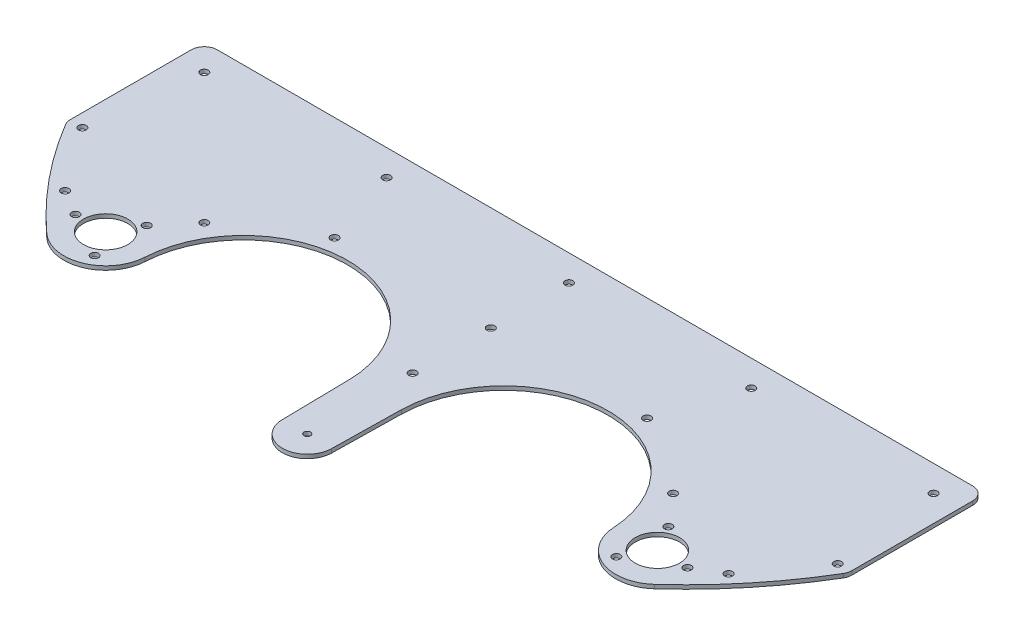
SolidWorks part; units mm, degrees
material "3.0205 (EN-AW 1200)"
ref_plane "Plan de face" through (0, 0, 0) normal (0, 0, 1) x (1, 0, 0)
ref_plane "Plan de dessus" through (0, 0, 0) normal (0, 1, 0) x (1, 0, 0)
ref_plane "Plan de droite" through (0, 0, 0) normal (1, 0, 0) x (0, 0, -1)
sketch "Esquisse1" plane through (0, 0, 0) normal (0, 1, 0) x (1, 0, 0)
  line L0 (0, 0) -> (0, -155) construction
  line L1 (-150, -35) -> (150, -35)
  line L2 (-150, -35) -> (-150, -87.758)
  line L3 (-150, -155) -> (0, -155) construction
  line L7 (-10.0061, -119.3019) -> (-9.5467, -145.6184)
  line L8 (10.0061, -119.3019) -> (9.5467, -145.6184)
  line L11 (150, -35) -> (150, -87.758)
  circle A0 centre (-70, -45) radius 1.5
  circle A1 centre (0, -45) radius 1.5
  circle A2 centre (105.917, -116.9526) radius 8.5
  arc A3 (150, -87.758) -> (116.6574, -128.812) centre (0, 0) cw
  arc A4 (116.6574, -128.812) -> (89.9407, -117.8233) centre (105.917, -116.9526) cw
  circle A5 centre (-105.917, -116.9526) radius 8.5
  circle A6 centre (-100.1435, -106.9526) radius 1.5
  circle A7 centre (70, -45) radius 1.5
  circle A8 centre (-100.1435, -126.9526) radius 1.5
  circle A9 centre (-117.464, -116.9526) radius 1.5
  circle A10 centre (100.1435, -126.9526) radius 1.5
  circle A11 centre (117.464, -116.9526) radius 1.5
  circle A12 centre (-140, -45) radius 1.5
  circle A13 centre (140, -45) radius 1.5
  arc A14 (-9.5467, -145.6184) -> (9.5467, -145.6184) centre (0, -145.4518) ccw
  arc A15 (-116.6574, -128.812) -> (-89.9407, -117.8233) centre (-105.917, -116.9526) ccw
  arc A16 (-150, -87.758) -> (-116.6574, -128.812) centre (0, 0) ccw
  arc A17 (-10.0061, -119.3019) -> (-89.9407, -117.8233) centre (-50, -120) ccw
  arc A18 (10.0061, -119.3019) -> (89.9407, -117.8233) centre (50, -120) cw
  circle A19 centre (100.1435, -106.9526) radius 1.5
  circle A20 centre (0, -145.4518) radius 1.25
  circle A21 centre (-60, -75) radius 1.5
  circle A22 centre (-90, -95) radius 1.5
  arc A23 (-164.4636, -56.1533) -> (-113.5142, -131.5903) centre (0, 0) ccw construction
  circle A24 centre (90, -95) radius 1.5
  circle A25 centre (60, -75) radius 1.5
  circle A26 centre (0, -105) radius 1.5
  circle A27 centre (0, -75) radius 1.5
  circle A28 centre (145, -86.8101) radius 1.5
  circle A29 centre (127.3662, -111.0804) radius 1.5
  circle A30 centre (0, 0) radius 169 construction
  circle A31 centre (-127.3662, -111.0804) radius 1.5
  circle A32 centre (-145, -86.8101) radius 1.5
  point P28 (-105.917, -116.9526)
  point P40 (0, -35)
  dimension "D2" = 70
  dimension "D3" = 10
  dimension "D4" = 3
  dimension "D5" = 45
  dimension "D7" = 100
  dimension "D8" = 16
  dimension "D10" = 17
  dimension "D11" = 20
  dimension "D12" = 40
  dimension "D15" = 70
  dimension "D16" = 20
  dimension "D17" = 9.5482
  dimension "D18" = 2.5
  dimension "D19" = 30
  dimension "D14" = 120
  dimension "D21" = 300
  dimension "D22" = 3
  dimension "D9" = 3
  dimension "D13" = 3
  dimension "D23" = 60
  dimension "D25" = 60
  dimension "D26" = 70
  dimension "D27" = 30
  dimension "D28" = 3
  dimension "D29" = 30
  dimension "D30" = 145
  dimension "D31" = 338
  dimension "D6" = 155
  dimension "D20" = 1
  dimension "D24" = 35
extrude "Boss.-Extru.1" add sketch "Esquisse1" along normal blind 1.5
fillet "Congé1" radius 5 4 edges at (-150, 0.75, 35) (150, 0.75, 35) (-150, 0.75, 87.758) (150, 0.75, 87.758)
